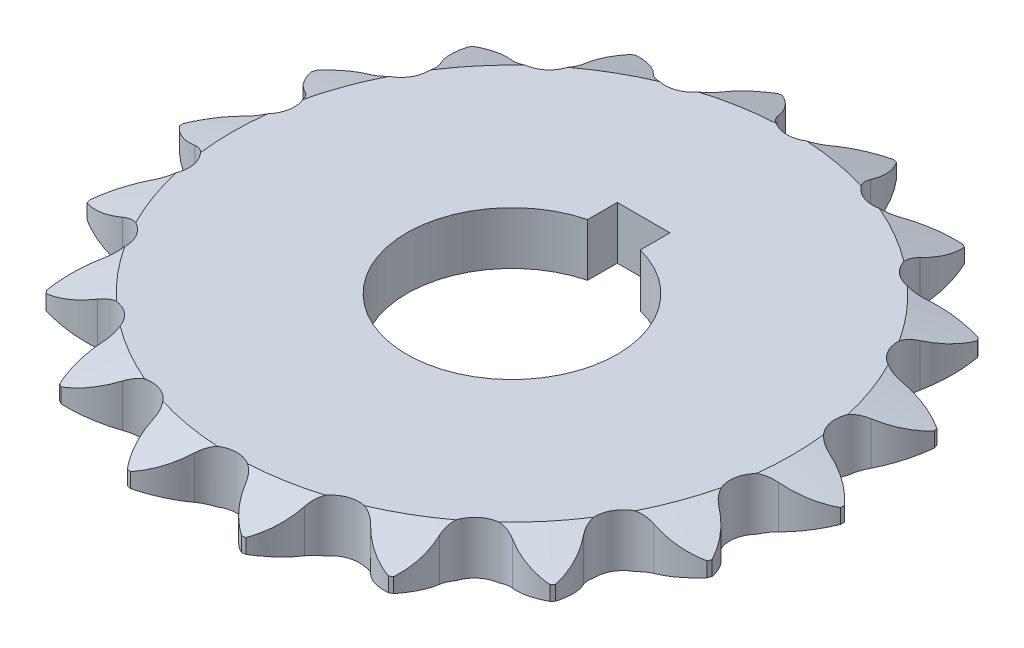
SolidWorks part; units mm, degrees
ref_plane "Front Plane" through (0, 0, 0) normal (0, 0, 1) x (1, 0, 0)
ref_plane "Top Plane" through (0, 0, 0) normal (0, 1, 0) x (1, 0, 0)
ref_plane "Right Plane" through (0, 0, 0) normal (1, 0, 0) x (0, 0, -1)
sketch "Sketch1" plane through (0, 0, 0) normal (0, 1, 0) x (1, 0, 0)
  circle A0 centre (0, 0) radius 19.939
  dimension "D1" = 39.878
extrude "Base Circle" add sketch "Sketch1" along normal mid plane 3.175
sketch "Sketch2" plane through (0, 1.5875, 0) normal (0, 1, 0) x (1, 0, 0)
  line L0 (0, 0) -> (0, 18.288) construction
  line L1 (0, 18.288) -> (-6.2549, 17.1851) construction
  line L2 (-6.2549, 17.1851) -> (0, 0) construction
  line L3 (0, 0) -> (-3.1274, 17.7365) construction
  circle A0 centre (0, 0) radius 18.288 construction
  circle A2 centre (0, 0) radius 16.7701 construction
  arc A3 (-2.256, 12.7943) -> (-3.4797, 19.7346) centre (-5.7357, 15.7588) ccw construction
  arc A4 (-3.4797, 19.7346) -> (-2.256, 12.7943) centre (0, 16.7701) ccw construction
  circle A5 centre (0, 0) radius 20.039 construction
  circle A6 centre (0, 0) radius 19.939 construction
  arc A7 (3.3468, 19.6561) -> (-3.3468, 19.6561) centre (0, 0) ccw
  arc A8 (-3.3468, 19.6561) -> (-1.5531, 17.6032) centre (-5.7357, 15.7588) cw
  arc A9 (3.3468, 19.6561) -> (1.5531, 17.6032) centre (5.7357, 15.7588) ccw
  arc A10 (-1.5531, 17.6032) -> (1.5531, 17.6032) centre (0, 18.288) ccw
  dimension "D1" = 36.576
  dimension "D2" = 1.6974
  dimension "D4" = 0.1
  dimension "D3" = 20
extrude "Tooth profile Cut" cut sketch "Sketch2" against normal through all both and the other way through all
pattern_circular "Tooth Profile Cut Patterns" count 18 over 360 about axis through (0, 0, 0) along (0, 1, 0) of "Tooth profile Cut"
sketch "Sketch3" plane through (0, 0, 0) normal (1, 0, 0) x (0, 0, -1)
  line L0 (0.1173, 0) -> (20.0563, 0) construction
  line L1 (0.1173, -1.5875) -> (0.1173, 1.5875) construction
  line L2 (20.0563, -0.3969) -> (20.0563, 0.3969) construction
  line L3 (20.0563, -0.3969) -> (16.8813, -1.5875)
  line L4 (16.8813, -1.5875) -> (16.8813, 1.5875) construction
  line L5 (16.8813, 1.5875) -> (20.0563, 0.3969)
  line L6 (20.0563, 0.3969) -> (20.0563, 1.5875)
  line L7 (20.0563, 1.5875) -> (16.8813, 1.5875)
  line L8 (20.0563, -0.3969) -> (20.0563, -1.5875)
  line L9 (20.0563, -1.5875) -> (16.8813, -1.5875)
  point P6 (20.0563, 0)
  dimension "D1" = 19.939
  dimension "D2" = 0.7937
  dimension "D3" = 3.175
  dimension "D4" = 3.175
revolve "Tooth Chamfer" cut sketch "Sketch3" angle 360 about axis through (0, 1.5875, 0) along (0, -1, 0)
sketch "Sketch4" plane through (0, -1.5875, 0) normal (0, -1, 0) x (1, 0, 0)
  line L0 (0, -6.35) -> (0, -7.9375) construction
  line L1 (0, -7.9375) -> (1.5875, -7.9375)
  line L2 (1.5875, -7.9375) -> (1.5875, -6.1484)
  line L3 (0, -7.9375) -> (-1.5875, -7.9375)
  line L4 (-1.5875, -7.9375) -> (-1.5875, -6.1484)
  arc A0 (1.5875, -6.1484) -> (-1.5875, -6.1484) centre (0, 0) ccw
  dimension "D1" = 12.7
  dimension "D2" = 1.5875
  dimension "D3" = 6.35
extrude "Shaft hole with keyway" cut sketch "Sketch4" against normal through all both and the other way through all
